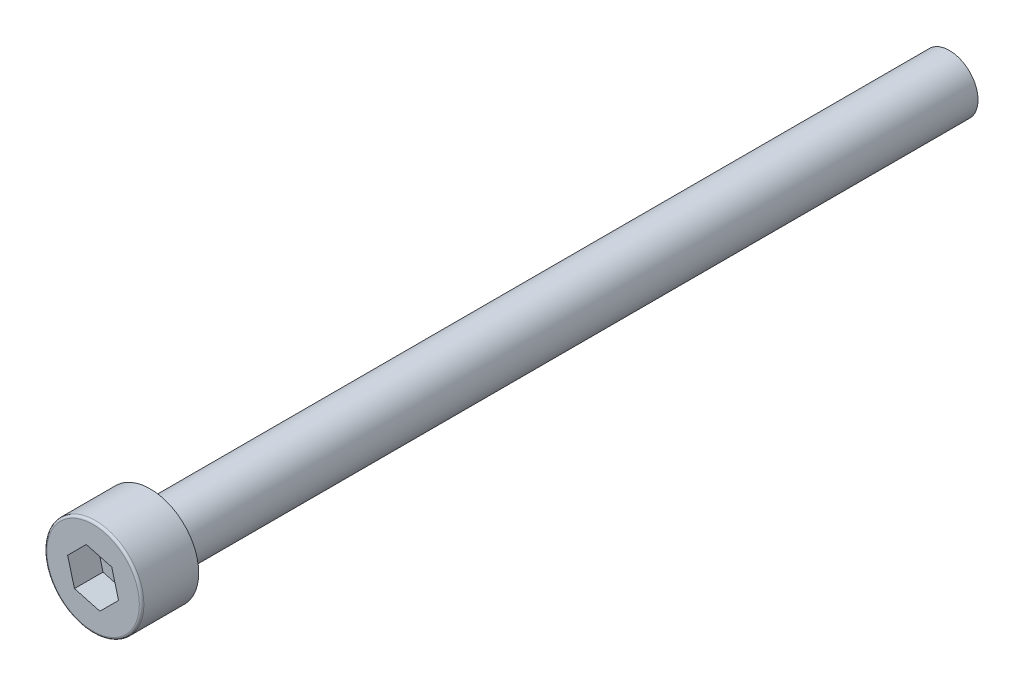
SolidWorks part; units mm, degrees
ref_plane "前视基准面" through (0, 0, 0) normal (0, 0, 1) x (1, 0, 0)
ref_plane "上视基准面" through (0, 0, 0) normal (0, 1, 0) x (1, 0, 0)
ref_plane "右视基准面" through (0, 0, 0) normal (1, 0, 0) x (0, 0, -1)
sketch "草图1" plane through (0, 0, 0) normal (0, 0, 1) x (1, 0, 0)
  circle A0 centre (0, 0) radius 4.25
  dimension "D1" = 8.5
extrude "凸台-拉伸1" add sketch "草图1" along normal blind 5
sketch "草图2" plane through (0, 0, 5) normal (0, 0, 1) x (1, 0, 0)
  line L1 (-1.633, -1.633) -> (0.5977, -2.2307)
  line L2 (0.5977, -2.2307) -> (2.2307, -0.5977)
  line L3 (2.2307, -0.5977) -> (1.633, 1.633)
  line L4 (1.633, 1.633) -> (-0.5977, 2.2307)
  line L5 (-0.5977, 2.2307) -> (-2.2307, 0.5977)
  line L6 (-2.2307, 0.5977) -> (-1.633, -1.633)
  circle A0 centre (0, 0) radius 2 construction
  dimension "D1" = 4
extrude "切除-拉伸1" cut sketch "草图2" against normal blind 2.5
sketch "草图3" plane through (0, 0, 0) normal (0, 0, -1) x (-1, 0, 0)
  circle A0 centre (0, 0) radius 2.5
  dimension "D1" = 5
extrude "凸台-拉伸2" add sketch "草图3" along normal blind 70
fillet "圆角1" radius 0.2 1 edges at (4.25, 0, 5)
